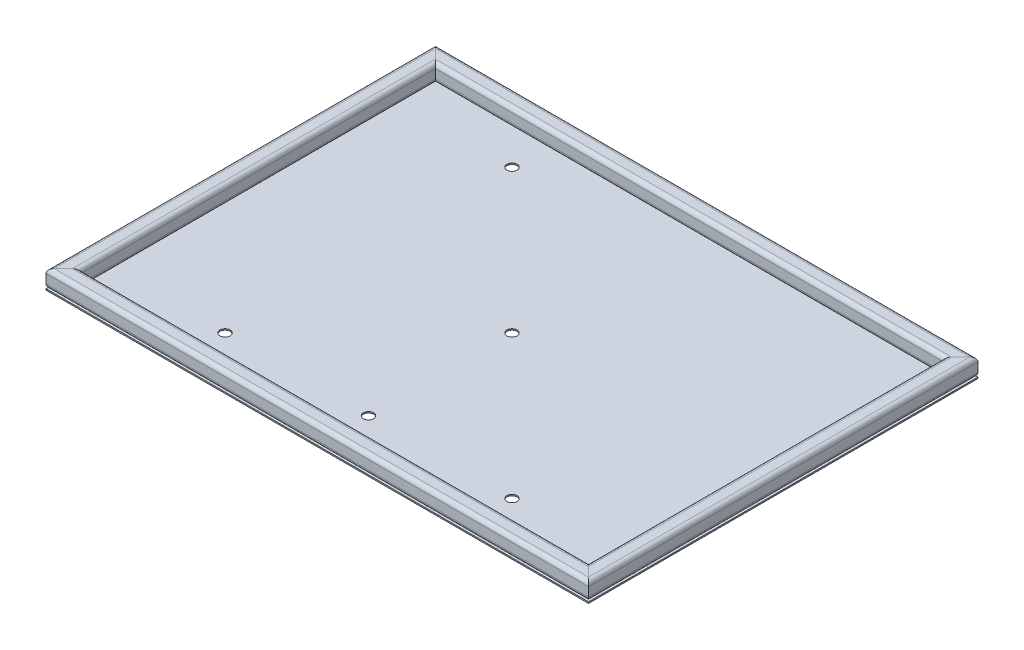
SolidWorks part; units mm, degrees
ref_plane "Alzado" through (0, 0, 0) normal (0, 0, 1) x (1, 0, 0)
ref_plane "Planta" through (0, 0, 0) normal (0, 1, 0) x (1, 0, 0)
ref_plane "Vista lateral" through (0, 0, 0) normal (1, 0, 0) x (0, 0, -1)
sketch "Croquis1" plane through (0, 0, 0) normal (0, 1, 0) x (1, 0, 0)
  line L1 (-397, 285) -> (397, 285)
  line L2 (-397, 285) -> (-397, -285)
  line L3 (-397, -285) -> (397, -285)
  line L4 (397, 285) -> (397, -285)
  line L5 (-397, 285) -> (397, -285) construction
  line L6 (-397, -285) -> (397, 285) construction
  point P0 (0, 0)
  dimension "D1" = 570
  dimension "D2" = 794
other "Tubo cuadrado 2 X 2 X 0.25(1)"
ref_plane "Plano1" through (-384.3, 12.7, -285) normal (0, 0, 1) x (1, 0, 0)
sketch "Sketch1" plane through (-384.3, 12.7, -285) normal (0, 0, 1) x (1, 0, 0)
  line L0 (-6.7, -9.7) -> (6.7, -9.7)
  line L1 (-9.7, -6.7) -> (-9.7, 6.7)
  line L2 (6.7, 9.7) -> (-6.7, 9.7)
  line L3 (9.7, 6.7) -> (9.7, -6.7)
  line L4 (-6.7, -12.7) -> (6.7, -12.7)
  line L5 (-12.7, -6.7) -> (-12.7, 6.7)
  line L6 (6.7, 12.7) -> (-6.7, 12.7)
  line L7 (12.7, 6.7) -> (12.7, -6.7)
  line L8 (0, 0) -> (9.7, 0) construction
  line L9 (0, 0) -> (0, 9.7) construction
  arc A0 (12.7, 6.7) -> (6.7, 12.7) centre (6.7, 6.7) ccw
  arc A1 (6.7, -12.7) -> (12.7, -6.7) centre (6.7, -6.7) ccw
  arc A2 (-12.7, -6.7) -> (-6.7, -12.7) centre (-6.7, -6.7) ccw
  arc A3 (-6.7, 12.7) -> (-12.7, 6.7) centre (-6.7, 6.7) ccw
  arc A4 (-6.7, 9.7) -> (-9.7, 6.7) centre (-6.7, 6.7) ccw
  arc A5 (9.7, 6.7) -> (6.7, 9.7) centre (6.7, 6.7) ccw
  arc A6 (6.7, -9.7) -> (9.7, -6.7) centre (6.7, -6.7) ccw
  arc A7 (-9.7, -6.7) -> (-6.7, -9.7) centre (-6.7, -6.7) ccw
  point P3 (0, 12.7)
  point P4 (12.7, 0)
  point P5 (0, -12.7)
  point P6 (-12.7, 0)
  point P7 (-12.7, 12.7)
  point P8 (-12.7, -12.7)
  point P33 (0, 0)
  point P35 (12.7, -12.7)
  point P36 (12.7, 12.7)
  point P37 (0, 0)
  dimension "D1" = 6
  dimension "Thickness" = 3
  dimension "V_leg" = 25.4
sketch "Croquis3" plane through (0, 0, 0) normal (0, -1, 0) x (1, 0, 0)
  line L1 (397, 285) -> (-397, 285)
  line L2 (397, 285) -> (397, -285)
  line L3 (397, -285) -> (-397, -285)
  line L4 (-397, 285) -> (-397, -285)
  line L5 (397, 285) -> (-397, -285) construction
  line L6 (397, -285) -> (-397, 285) construction
  point P0 (0, 0)
extrude "Saliente-Extruir1" add sketch "Croquis3" along normal blind 1.9 separate body
ref_plane "Plano2" through (0, 0, 210) normal (0, 0, 1) x (1, 0, 0)
sketch "Croquis4" plane through (0, -1128.704, 0) normal (0, 1, 0) x (1, 0, 0)
  circle A0 centre (2010, 436.4137) radius 8.0354
sketch "Croquis5" plane through (0, 0, 0) normal (0, 1, 0) x (1, 0, 0)
  circle A0 centre (233, -210.2449) radius 3.1562
  circle A1 centre (210, -210) radius 7.8426
  circle A2 centre (187, -209.7551) radius 3.1812
  circle A3 centre (0, -210) radius 7.9375
  circle A4 centre (-23, -209.7551) radius 3.175
  circle A5 centre (23, -210.2449) radius 3.244
  circle A6 centre (-233, -209.7551) radius 3.175
  circle A7 centre (-210, -210) radius 7.9375
  circle A8 centre (-187, -210.2449) radius 3.175
sketch "Croquis6" plane through (0, -1.9, 0) normal (0, -1, 0) x (1, 0, 0)
  line L0 (-397, -210) -> (-210, -210) construction
  line L1 (-397, 285) -> (-397, -285) construction
  line L2 (-210, -210) -> (-210, -285) construction
  line L3 (-397, -285) -> (397, -285) construction
  line L4 (-397, 210) -> (-210, 210) construction
  line L5 (-397, 285) -> (-397, -285) construction
  line L6 (-210, 210) -> (-210, 285) construction
  line L7 (397, 285) -> (-397, 285) construction
  line L8 (-210, 210) -> (1.2, 210) construction
  line L9 (1.2, 210) -> (210, 210) construction
  line L10 (397, 210) -> (-397, 210) construction
  line L11 (397, -285) -> (397, 285) construction
  line L12 (-397, 210) -> (0, 210) construction
  line L13 (0, 210) -> (0, -18.3406) construction
  circle A0 centre (0, 0) radius 7.5
  circle A1 centre (210, 210) radius 7.5
  circle A2 centre (1.2, 210) radius 9 construction
  circle A3 centre (-210, 210) radius 7.5
  circle A4 centre (-210, -210) radius 7.5
  circle A5 centre (0, 210) radius 7.5
  dimension "D7" = 15
  dimension "D9" = 15
  dimension "D10" = 15
  dimension "D11" = 15
  dimension "D12" = 15
  dimension "D3" = 210
  dimension "D5" = 210
  dimension "D2" = 187
  dimension "D1" = 75
  dimension "D4" = 75
extrude "Cortar-Extruir2" cut sketch "Croquis6" against normal blind 10
